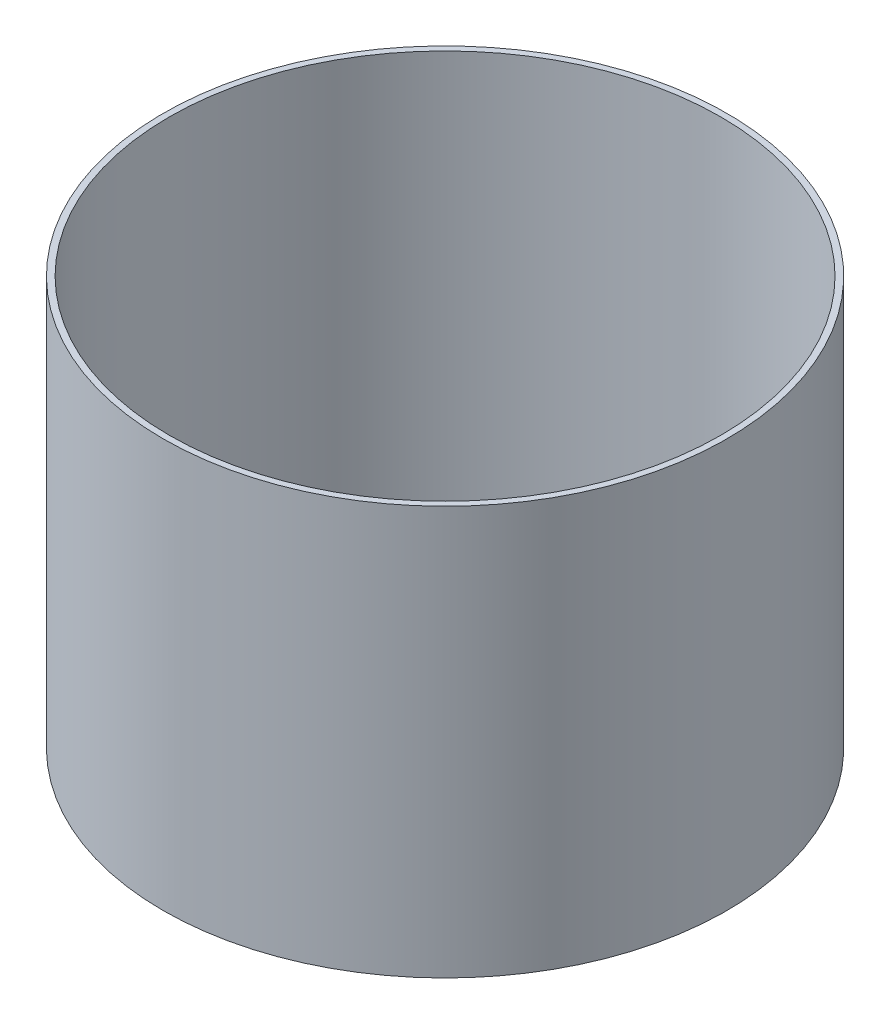
SolidWorks part; units mm, degrees
material "AISI 1035 Steel (SS)"
ref_plane "Front Plane" through (0, 0, 0) normal (0, 0, 1) x (1, 0, 0)
ref_plane "Top Plane" through (0, 0, 0) normal (0, 1, 0) x (1, 0, 0)
ref_plane "Right Plane" through (0, 0, 0) normal (1, 0, 0) x (0, 0, -1)
sketch "Sketch2" plane through (0, 0, 0) normal (0, 1, 0) x (1, 0, 0)
  circle A0 centre (0, 0) radius 690
  circle A1 centre (0, 0) radius 675
  dimension "D1" = 1380
  dimension "D2" = 1350
extrude "Boss-Extrude1" add sketch "Sketch2" along normal blind 1000
